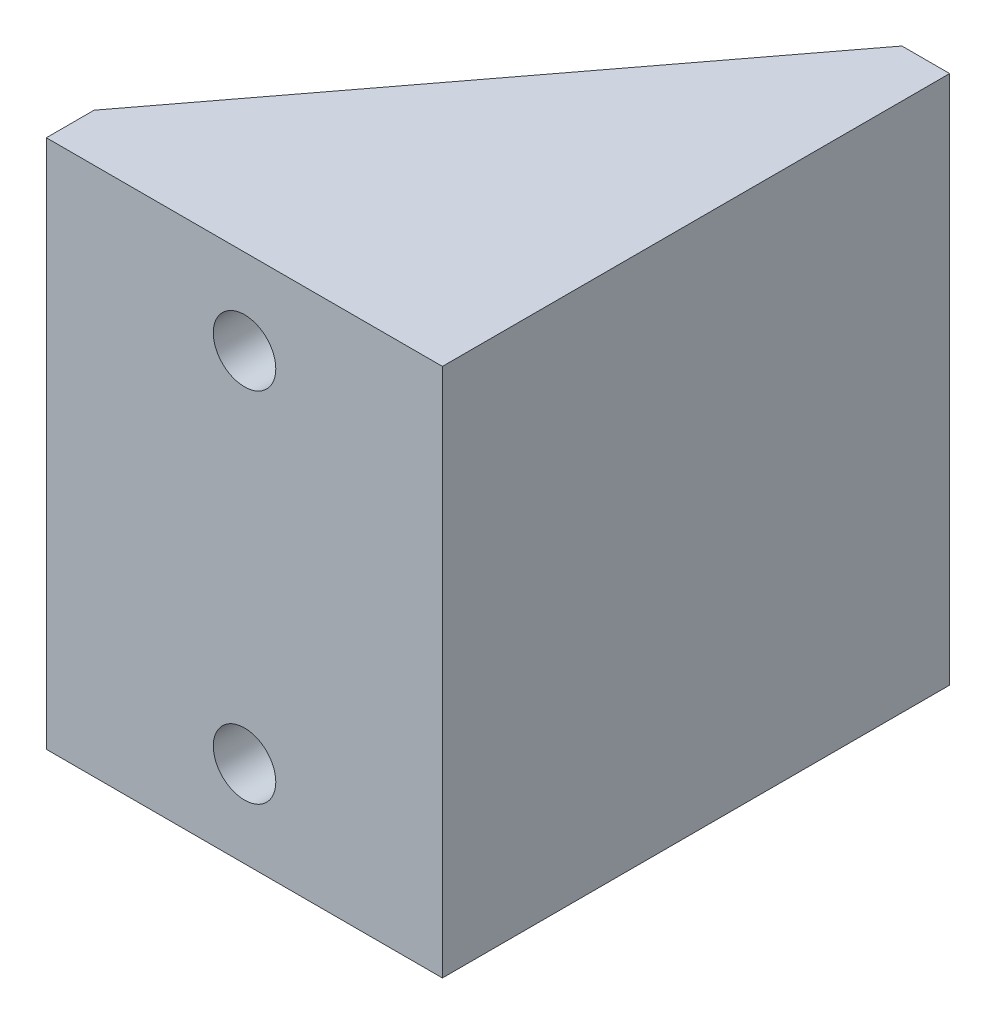
SolidWorks part; units mm, degrees
ref_plane "Front Plane" through (0, 0, 0) normal (0, 0, 1) x (1, 0, 0)
ref_plane "Top Plane" through (0, 0, 0) normal (0, 1, 0) x (1, 0, 0)
ref_plane "Right Plane" through (0, 0, 0) normal (1, 0, 0) x (0, 0, -1)
sketch "Sketch1" plane through (0, 0, 0) normal (0, 0, 1) x (1, 0, 0)
  line L1 (-21.082, -28.194) -> (21.082, -28.194)
  line L2 (-21.082, -28.194) -> (-21.082, 28.194)
  line L3 (-21.082, 28.194) -> (21.082, 28.194)
  line L4 (21.082, -28.194) -> (21.082, 28.194)
  line L5 (-21.082, -28.194) -> (21.082, 28.194) construction
  line L6 (-21.082, 28.194) -> (21.082, -28.194) construction
  point P0 (0, 0)
  dimension "D1" = 56.388
  dimension "D2" = 42.164
extrude "Boss-Extrude1" add sketch "Sketch1" along normal blind 5.08
sketch "Sketch2" plane through (21.082, 0, 0) normal (1, 0, 0) x (0, 0, -1)
  line L0 (-5.08, 28.194) -> (0, 28.194) construction
  line L1 (-5.08, -28.194) -> (48.92, -28.194)
  line L2 (-5.08, -28.194) -> (-5.08, 28.194)
  line L3 (-5.08, 28.194) -> (48.92, 28.194)
  line L4 (48.92, -28.194) -> (48.92, 28.194)
  line L5 (48.92, 18.779) -> (48.92, -19.021) construction
  dimension "D1" = 0
  dimension "D2" = 0
extrude "Boss-Extrude2" add sketch "Sketch2" against normal blind 5.08
sketch "Sketch3" plane through (0, 0, 5.08) normal (0, 0, 1) x (1, 0, 0)
  circle A0 centre (0.0164, 19.1029) radius 3.3274
  circle A1 centre (0.0164, -18.9971) radius 3.3274
extrude "Cut-Extrude1" cut sketch "Sketch3" against normal blind 5.08
sketch "Sketch4" plane through (0, 28.194, 0) normal (0, 1, 0) x (1, 0, 0)
  line L0 (16.002, 48.92) -> (-21.082, 0)
  line L1 (16.002, 48.92) -> (16.002, 0)
  line L2 (16.002, 0) -> (-21.082, 0)
extrude "Boss-Extrude3" add sketch "Sketch4" against normal blind 5.08
sketch "Sketch5" plane through (0, 0, 0) normal (0, 0, -1) x (-1, 0, 0)
  line L0 (0, 0) -> (28.5477, 0) construction
  line L1 (28.5477, 0) -> (-36.271, 0) construction
ref_plane "Plane1" through (0, 0, 0) normal (0, -1, 0) x (-1, 0, 0)
mirror "Mirror1" about plane through (0, 0, 0) normal (0, -1, 0) of "Boss-Extrude3"
